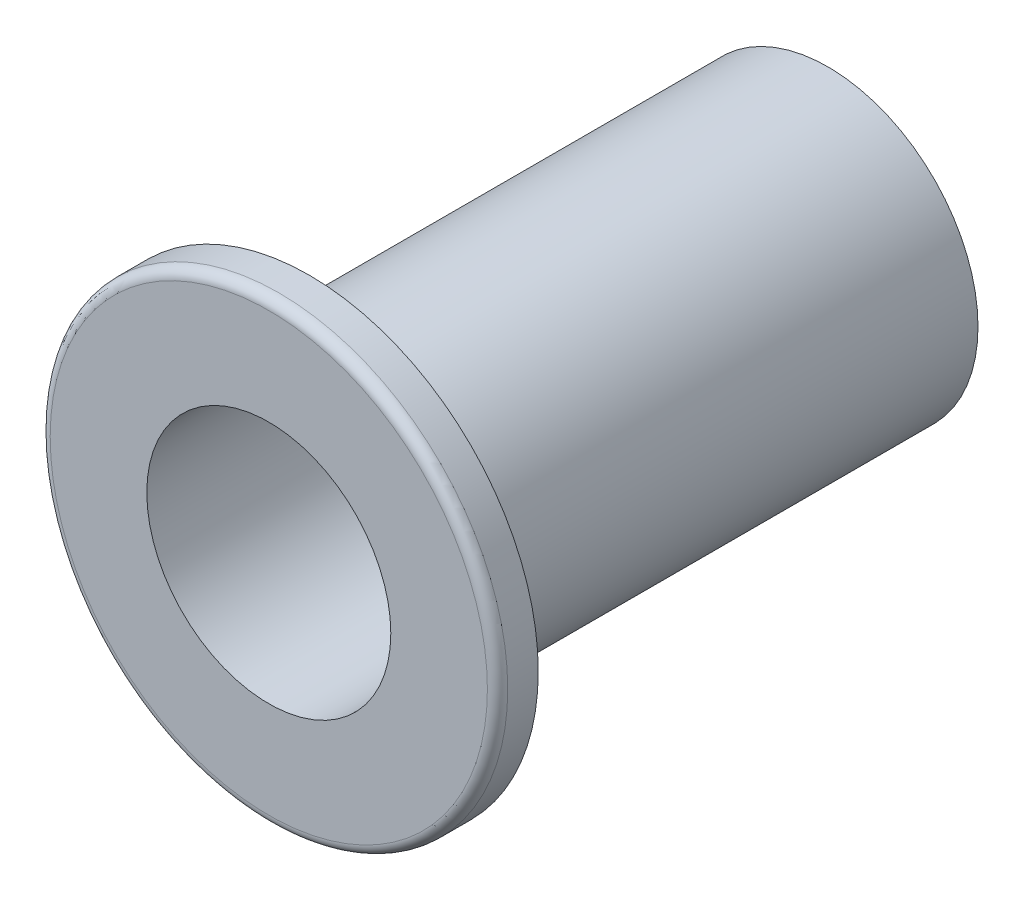
SolidWorks part; units mm, degrees
material "AISI 304"
ref_plane "前视基准面" through (0, 0, 0) normal (0, 0, 1) x (1, 0, 0)
ref_plane "上视基准面" through (0, 0, 0) normal (0, 1, 0) x (1, 0, 0)
ref_plane "右视基准面" through (0, 0, 0) normal (1, 0, 0) x (0, 0, -1)
sketch "草图1" plane through (0, 0, 0) normal (1, 0, 0) x (0, 0, -1)
  line L0 (0, 0) -> (6.0548, 0) construction
  line L1 (0, 2.95) -> (0, 4.5)
  line L2 (0, 4.5) -> (-0.8, 4.5)
  line L3 (-0.8, 4.5) -> (-0.8, 2.4)
  line L5 (10.2, 2) -> (10.2, 2.95)
  line L6 (10.2, 2.95) -> (0, 2.95)
  line L9 (4.2, 2) -> (10.2, 2)
  line L10 (4.2, 2) -> (4.2, 2.4)
  line L11 (4.2, 2.4) -> (-0.8, 2.4)
  dimension "D1" = 9
  dimension "D2" = 5.9
  dimension "D3" = 4
  dimension "D4" = 6
  dimension "D5" = 0.8
  dimension "D6" = 11
  dimension "D7" = 4.8
revolve "旋转1" add sketch "草图1" angle 360 about L0
fillet "圆角1" radius 0.2 1 edges at (4.5, 0, 0.8)
